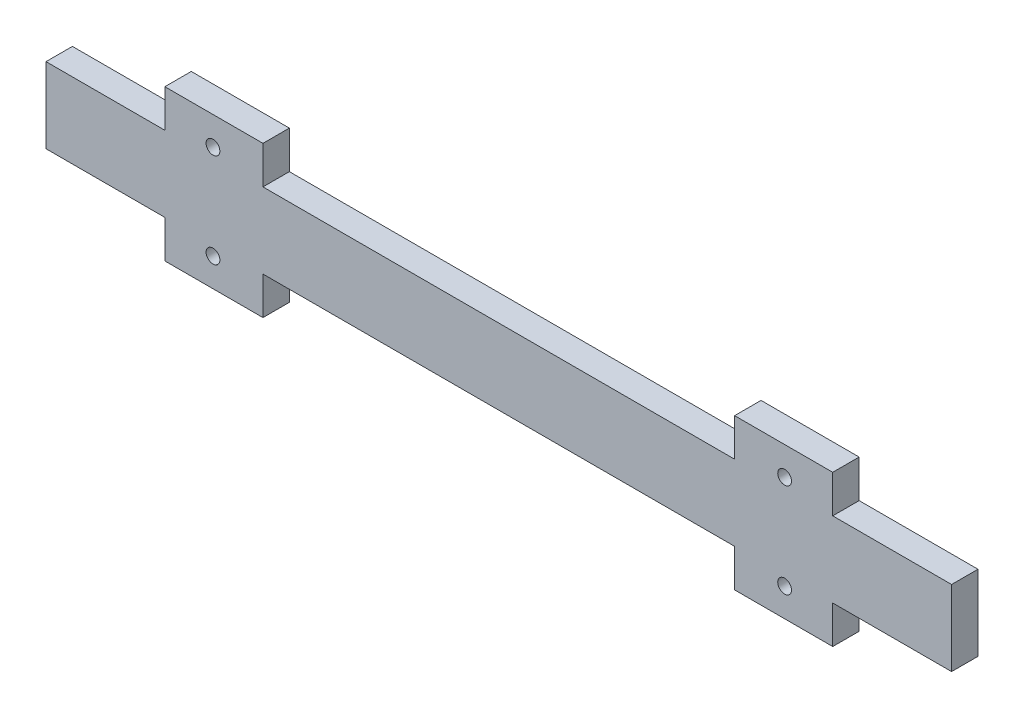
SolidWorks part; units mm, degrees
ref_plane "Alzado" through (0, 0, 0) normal (0, 0, 1) x (1, 0, 0)
ref_plane "Planta" through (0, 0, 0) normal (0, 1, 0) x (1, 0, 0)
ref_plane "Vista lateral" through (0, 0, 0) normal (1, 0, 0) x (0, 0, -1)
sketch "Sketch2" plane through (0, 0, 0) normal (0, 0, 1) x (1, 0, 0)
  line L0 (-56.9681, -20) -> (-56.9681, 20)
  line L1 (55, 0) -> (-55, 0) construction
  line L2 (-56.9681, 20) -> (6.0319, 20)
  line L3 (6.0319, 20) -> (6.0319, 40)
  line L4 (6.0319, 40) -> (58.0319, 40)
  line L5 (58.0319, 40) -> (58.0319, 20)
  line L6 (58.0319, 20) -> (308.0319, 20)
  line L7 (308.0319, 20) -> (308.0319, 40)
  line L8 (308.0319, 40) -> (360.0319, 40)
  line L9 (360.0319, 40) -> (360.0319, 20)
  line L10 (360.0319, 20) -> (423.0319, 20)
  line L11 (423.0319, 20) -> (423.0319, -20)
  line L13 (360.0319, -20) -> (423.0319, -20)
  line L14 (360.0319, -40) -> (360.0319, -20)
  line L15 (308.0319, -40) -> (360.0319, -40)
  line L16 (308.0319, -20) -> (308.0319, -40)
  line L17 (58.0319, -20) -> (308.0319, -20)
  line L18 (58.0319, -40) -> (58.0319, -20)
  line L19 (6.0319, -40) -> (58.0319, -40)
  line L20 (6.0319, -20) -> (6.0319, -40)
  line L21 (-56.9681, -20) -> (6.0319, -20)
  dimension "D1" = 40
  dimension "D2" = 63
  dimension "D3" = 52
  dimension "D4" = 63
  dimension "D5" = 52
  dimension "D6" = 40
  dimension "D7" = 40
  dimension "D8" = 80
  dimension "D9" = 80
  dimension "D10" = 480
extrude "Boss-Extrude1" add sketch "Sketch2" along normal blind 14
sketch "Sketch3" plane through (0, 0, 14) normal (0, 0, 1) x (1, 0, 0)
  line L0 (7.7, 0) -> (-7.7, 0) construction
  line L2 (58.0319, 20) -> (58.0319, 40) construction
  circle A5 centre (31.5319, 25) radius 3.65
  circle A6 centre (31.5319, -25) radius 3.65
  circle A11 centre (334.5319, -25) radius 3.65
  circle A12 centre (334.5319, 25) radius 3.65
  dimension "D9" = 7.3
  dimension "D10" = 26.5
  dimension "D11" = 25
extrude "Cut-Extrude1" cut sketch "Sketch3" against normal blind 14
